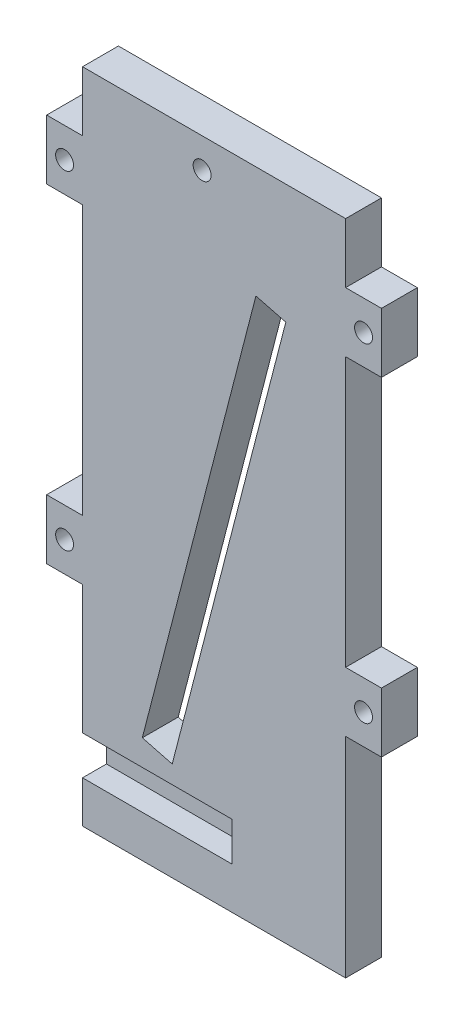
SolidWorks part; units mm, degrees
ref_plane "Plan de face" through (0, 0, 0) normal (0, 0, 1) x (1, 0, 0)
ref_plane "Plan de dessus" through (0, 0, 0) normal (0, 1, 0) x (1, 0, 0)
ref_plane "Plan de droite" through (0, 0, 0) normal (1, 0, 0) x (0, 0, -1)
sketch "Esquisse1" plane through (0, 0, 0) normal (0, 0, 1) x (1, 0, 0)
  line L0 (0, 80) -> (0, 90)
  line L1 (0, 0) -> (44, 0)
  line L2 (0, 0) -> (0, 15)
  line L3 (0, 90) -> (44, 90)
  line L4 (44, 0) -> (44, 15)
  line L5 (0, 80) -> (-6, 80)
  line L6 (44, 80) -> (44, 90)
  line L7 (0, 70) -> (-6, 70)
  line L8 (-6, 80) -> (-6, 70)
  line L9 (44, 80) -> (50, 80)
  line L10 (44, 25) -> (44, 70)
  line L11 (44, 70) -> (50, 70)
  line L12 (50, 80) -> (50, 70)
  line L13 (44, 15) -> (50, 15)
  line L14 (0, 25) -> (0, 70)
  line L15 (44, 25) -> (50, 25)
  line L16 (50, 15) -> (50, 25)
  line L17 (0, 15) -> (-6, 15)
  line L19 (0, 25) -> (-6, 25)
  line L20 (-6, 15) -> (-6, 25)
  dimension "D1" = 44
  dimension "D2" = 90
  dimension "D3" = 10
  dimension "D4" = 10
  dimension "D5" = 10
  dimension "D6" = 10
  dimension "D7" = 6
  dimension "D8" = 6
  dimension "D9" = 6
  dimension "D10" = 6
  dimension "D11" = 10
  dimension "D12" = 10
  dimension "D13" = 65
  dimension "D14" = 65
extrude "Boss.-Extru.1" add sketch "Esquisse1" along normal blind 6
sketch "Esquisse2" plane through (0, 0, 6) normal (0, 0, 1) x (1, 0, 0)
  line L0 (44, 90) -> (0, 90) construction
  line L1 (0, 15) -> (0, 0) construction
  circle A0 centre (20, 85) radius 1.5
  dimension "D1" = 3
  dimension "D2" = 5
  dimension "D3" = 20
extrude "Enlèv. mat.-Extru.1" cut sketch "Esquisse2" against normal blind 6
sketch "Esquisse5" plane through (0, 0, 0) normal (0, 0, -1) x (-1, 0, 0)
  line L0 (6, 25) -> (6, 15) construction
  line L1 (6, 80) -> (6, 70) construction
  line L2 (0, 80) -> (6, 80) construction
  line L3 (0, 25) -> (6, 25) construction
  line L4 (-22, 90) -> (-22, 0) construction
  line L5 (-44, 90) -> (0, 90) construction
  line L6 (0, 0) -> (-44, 0) construction
  circle A0 centre (3, 75) radius 1.5
  circle A1 centre (3, 20) radius 1.5
  circle A2 centre (-47, 20) radius 1.5
  circle A3 centre (-47, 75) radius 1.5
  dimension "D1" = 3
  dimension "D2" = 3
  dimension "D4" = 3
  dimension "D5" = 5
  dimension "D6" = 5
  dimension "D3" = 3
extrude "Enlèv. mat.-Extru.6" cut sketch "Esquisse5" against normal blind 6
sketch "Esquisse6" plane through (0, 0, 0) normal (0, 0, -1) x (-1, 0, 0)
  line L0 (-22, 90) -> (-22, 0) construction
  line L1 (-44, 90) -> (0, 90) construction
  line L2 (0, 0) -> (-44, 0) construction
  circle A0 centre (3, 20) radius 2.995
  circle A1 centre (3, 75) radius 2.995
  circle A2 centre (-47, 75) radius 2.995
  circle A3 centre (-47, 20) radius 2.995
  dimension "D1" = 5.99
  dimension "D2" = 5.99
extrude "Enlèv. mat.-Extru.7" cut sketch "Esquisse6" against normal blind 3
sketch "Esquisse9" plane through (0, 0, 6) normal (0, 0, 1) x (1, 0, 0)
  line L1 (0, 0) -> (44, 0)
  line L2 (0, 0) -> (0, -20)
  line L3 (0, -20) -> (44, -20)
  line L4 (44, 0) -> (44, -20)
  dimension "D1" = 44
  dimension "D2" = 20
extrude "Boss.-Extru.3" add sketch "Esquisse9" against normal blind 6
sketch "Esquisse10" plane through (0, 0, 6) normal (0, 0, 1) x (1, 0, 0)
  line L0 (0, 15) -> (0, -20) construction
  line L1 (0, -13) -> (25, -13)
  line L2 (0, -13) -> (0, -6.5)
  line L3 (0, -6.5) -> (25, -6.5)
  line L4 (25, -13) -> (25, -6.5)
  line L5 (0, -20) -> (44, -20) construction
  dimension "D1" = 7
  dimension "D2" = 6.5
  dimension "D3" = 25
extrude "Enlèv. mat.-Extru.9" cut sketch "Esquisse10" against normal blind 4
sketch "Esquisse11" plane through (0, 0, 6) normal (0, 0, 1) x (1, 0, 0)
  line L0 (29, 71.2925) -> (10, -2.2075)
  line L1 (10, -2.2075) -> (15, -3.5)
  line L2 (15, -3.5) -> (34, 70)
  line L3 (34, 70) -> (29, 71.2925)
  line L7 (44, 90) -> (0, 90) construction
  line L9 (44, 80) -> (44, 90) construction
  line L10 (44, 25) -> (44, 70) construction
  line L11 (0, 15) -> (0, -6.5) construction
  line L12 (25, -6.5) -> (0, -6.5) construction
  dimension "D1" = 10
  dimension "D2" = 15
  dimension "D3" = 10
  dimension "D4" = 3
  dimension "D5" = 20
extrude "Enlèv. mat.-Extru.11" cut sketch "Esquisse11" against normal blind 6
